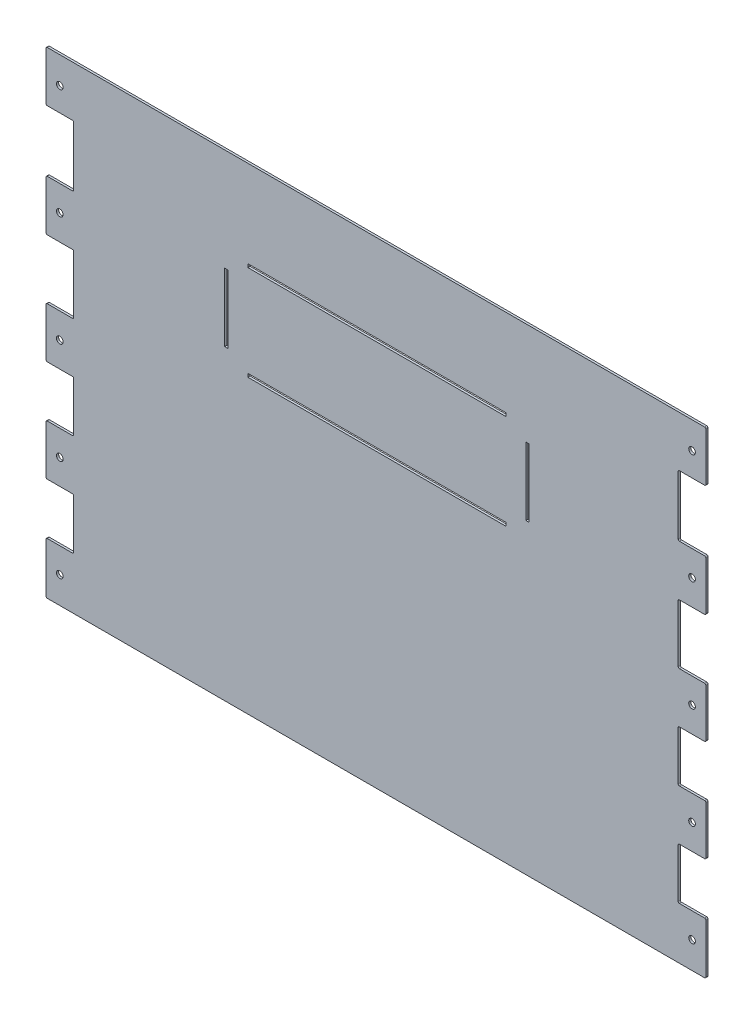
SolidWorks part; units mm, degrees
material "Alloy Steel"
ref_plane "X-Y Datum" through (0, 0, 0) normal (0, 0, 1) x (1, 0, 0)
ref_plane "X-Z Datum" through (0, 0, 0) normal (0, 1, 0) x (1, 0, 0)
ref_plane "Y-Z Datum" through (0, 0, 0) normal (1, 0, 0) x (0, 0, -1)
sketch "Sketch1" plane through (0, 0, 0) normal (0, 0, 1) x (1, 0, 0)
  line L0 (-6.604, -7.62) -> (-6.604, 104.0003) construction
  line L1 (21.9288, 0) -> (293.4706, 0) construction
  line L2 (1.016, 12.192) -> (1.016, 83.6803) construction
  line L3 (21.9288, 96.3803) -> (293.4706, 96.3803) construction
  line L4 (314.3834, 12.192) -> (314.3834, 83.6803) construction
  line L5 (-6.604, 104.0003) -> (322.0034, 104.0003) construction
  line L6 (322.0034, -7.62) -> (322.0034, 104.0003) construction
  line L7 (-6.604, -7.62) -> (322.0034, -7.62) construction
  line L8 (21.9288, 99.9363) -> (21.9288, 96.3803)
  line L10 (1.016, 83.6803) -> (1.016, 12.192)
  line L12 (-2.54, 83.6803) -> (-2.54, 12.192)
  line L13 (21.9288, 96.3803) -> (293.4706, 96.3803)
  line L15 (21.9288, 99.9363) -> (293.4706, 99.9363)
  line L18 (314.3834, 83.6803) -> (314.3834, 12.192)
  line L20 (317.9394, 83.6803) -> (317.9394, 12.192)
  line L21 (21.9288, 0) -> (293.4706, 0)
  line L23 (21.9288, -3.556) -> (293.4706, -3.556)
  line L25 (21.9288, 0) -> (21.9288, -3.556)
  line L26 (157.6997, 104.0003) -> (157.6997, 123.0101) construction
  line L27 (1.016, 96.3803) -> (314.3834, 96.3803) construction
  line L28 (1.016, 0) -> (314.3834, 0) construction
  line L29 (293.4706, 0) -> (293.4706, -3.556)
  line L30 (293.4706, 99.9363) -> (293.4706, 96.3803)
  line L31 (314.3834, 0) -> (314.3834, 96.3803) construction
  line L32 (1.016, 83.6803) -> (-2.54, 83.6803)
  line L33 (156.6144, 191.4284) -> (156.6144, 208.1281) construction
  line L34 (-2.54, 12.192) -> (1.016, 12.192)
  line L35 (317.9394, 12.192) -> (314.3834, 12.192)
  line L36 (314.3834, 83.6803) -> (317.9394, 83.6803)
  line L37 (1.016, 0) -> (1.016, 96.3803) construction
  line L38 (-190.4715, 191.4284) -> (503.7004, 191.4284)
  line L39 (-190.4715, 191.4284) -> (-190.4715, 138.3284)
  line L40 (-190.4715, -310.5137) -> (503.7004, -310.5137)
  line L41 (503.7004, 191.4284) -> (503.7004, 138.3284)
  line L42 (-190.4715, -201.978) -> (-161.3883, -201.978)
  line L43 (-190.4715, -256.0092) -> (-161.3883, -256.0092)
  line L44 (-161.3883, -201.978) -> (-161.3883, -256.0092)
  line L45 (-190.4715, -95.0858) -> (-161.3883, -95.0858)
  line L46 (-190.4715, -148.9426) -> (-161.3883, -148.9426)
  line L47 (-161.3883, -95.0858) -> (-161.3883, -148.9426)
  line L48 (-190.4715, 20.6298) -> (-161.3883, 20.6298)
  line L49 (-190.4715, -42.0779) -> (-161.3883, -42.0779)
  line L50 (-161.3883, 20.6298) -> (-161.3883, -42.0779)
  line L51 (-190.4715, 138.3284) -> (-161.3883, 138.3284)
  line L52 (-190.4715, 74.0417) -> (-161.3883, 74.0417)
  line L53 (-161.3883, 138.3284) -> (-161.3883, 74.0417)
  line L54 (503.7004, -256.0092) -> (474.6172, -256.0092)
  line L55 (474.6172, -201.978) -> (474.6172, -256.0092)
  line L56 (503.7004, -201.978) -> (474.6172, -201.978)
  line L57 (503.7004, -148.9426) -> (474.6172, -148.9426)
  line L58 (474.6172, -95.0858) -> (474.6172, -148.9426)
  line L59 (503.7004, -95.0858) -> (474.6172, -95.0858)
  line L60 (503.7004, -42.0779) -> (474.6172, -42.0779)
  line L61 (474.6172, 20.6298) -> (474.6172, -42.0779)
  line L62 (503.7004, 20.6298) -> (474.6172, 20.6298)
  line L63 (503.7004, 74.0417) -> (474.6172, 74.0417)
  line L64 (474.6172, 138.3284) -> (474.6172, 74.0417)
  line L65 (503.7004, 138.3284) -> (474.6172, 138.3284)
  line L66 (503.7004, 74.0417) -> (503.7004, 20.6298)
  line L67 (503.7004, -42.0779) -> (503.7004, -95.0858)
  line L68 (503.7004, -148.9426) -> (503.7004, -201.978)
  line L69 (503.7004, -256.0092) -> (503.7004, -310.5137)
  line L70 (-190.4715, -256.0092) -> (-190.4715, -310.5137)
  line L71 (-190.4715, -148.9426) -> (-190.4715, -201.978)
  line L72 (-190.4715, -42.0779) -> (-190.4715, -95.0858)
  line L73 (-190.4715, 74.0417) -> (-190.4715, 20.6298)
  circle A0 centre (-175.9935, 163.2534) radius 3.5
  circle A1 centre (-175.9935, 47.3358) radius 3.5
  circle A2 centre (-175.9935, -68.5819) radius 3.5
  circle A3 centre (-175.9935, -175.4603) radius 3.5
  circle A4 centre (-175.9935, -282.3387) radius 3.5
  circle A5 centre (489.2224, 163.2534) radius 3.5
  circle A6 centre (489.2224, 47.3358) radius 3.5
  circle A7 centre (489.2224, -68.5819) radius 3.5
  circle A8 centre (489.2224, -175.4603) radius 3.5
  circle A9 centre (489.2224, -282.3387) radius 3.5
  point P84 (0, 0)
  dimension "D1" = 7.62
  dimension "D2" = 313.3674
  dimension "D3" = 96.3803
  dimension "D4" = 3.556
  dimension "D5" = 3.556
extrude "Boss-Extrude1" add sketch "Sketch1" along normal blind 2.286
fillet "Fillet1" radius 1.27 36 edges at (-190.4715, 191.4284, 1.143) (-190.4715, 138.3284, 1.143) (-161.3883, 138.3284, 1.143) (-161.3883, 74.0417, 1.143) (-190.4715, 74.0417, 1.143) (-190.4715, 20.6298, 1.143) (-161.3883, 20.6298, 1.143) (-161.3883, -42.0779, 1.143) (-190.4715, -42.0779, 1.143) (-190.4715, -95.0858, 1.143) (-161.3883, -95.0858, 1.143) (-161.3883, -148.9426, 1.143) (-190.4715, -148.9426, 1.143) (-190.4715, -201.978, 1.143) (-161.3883, -201.978, 1.143) (-161.3883, -256.0092, 1.143) (-190.4715, -256.0092, 1.143) (-190.4715, -310.5137, 1.143) (503.7004, -310.5137, 1.143) (503.7004, -256.0092, 1.143) (474.6172, -256.0092, 1.143) (474.6172, -201.978, 1.143) (503.7004, -201.978, 1.143) (503.7004, -148.9426, 1.143) (474.6172, -148.9426, 1.143) (474.6172, -95.0858, 1.143) (503.7004, -95.0858, 1.143) (503.7004, -42.0779, 1.143) (474.6172, -42.0779, 1.143) (474.6172, 20.6298, 1.143) (503.7004, 20.6298, 1.143) (503.7004, 74.0417, 1.143) (474.6172, 74.0417, 1.143) (474.6172, 138.3284, 1.143) (503.7004, 138.3284, 1.143) (503.7004, 191.4284, 1.143)
